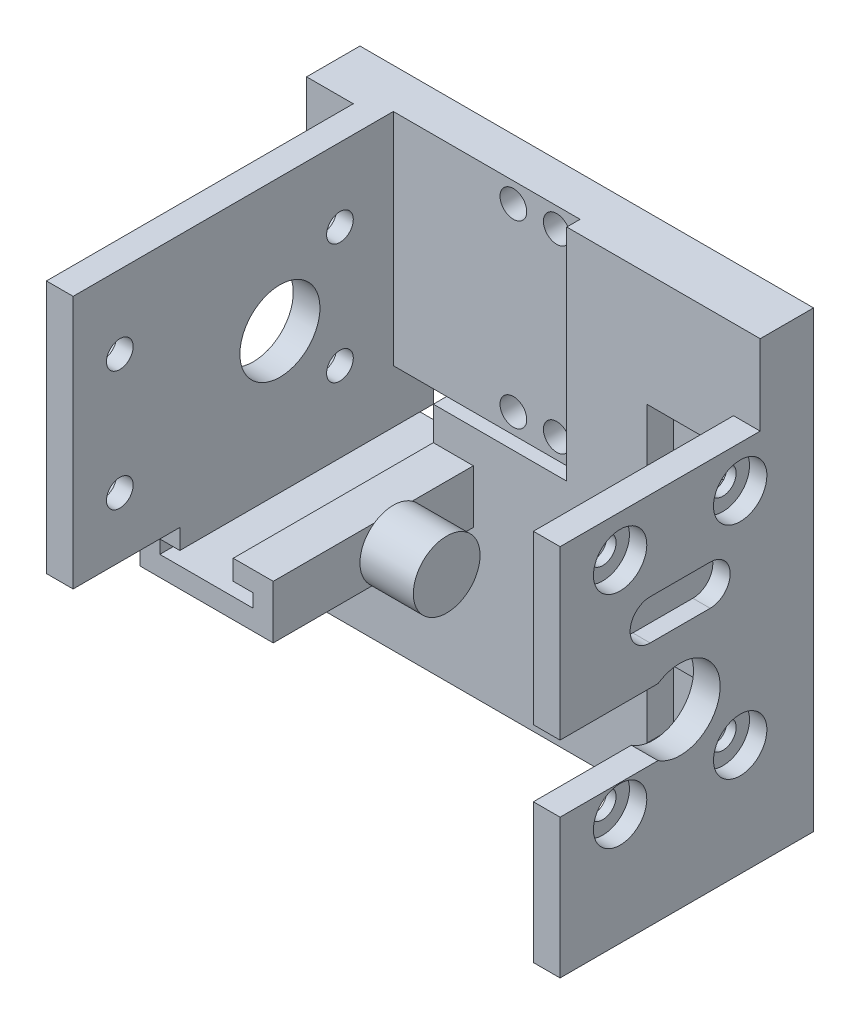
SolidWorks part; units mm, degrees
material "ABS PC"
ref_plane "Front Plane" through (0, 0, 0) normal (0, 0, 1) x (1, 0, 0)
ref_plane "Top Plane" through (0, 0, 0) normal (0, 1, 0) x (1, 0, 0)
ref_plane "Right Plane" through (0, 0, 0) normal (1, 0, 0) x (0, 0, -1)
sketch "Sketch1" plane through (0, 0, 0) normal (0, 0, 1) x (1, 0, 0)
  line L0 (0, 0) -> (0, 60)
  line L1 (0, 60) -> (68, 60)
  line L2 (68, 60) -> (68, 0)
  line L3 (68, 0) -> (0, 0)
  dimension "D1" = 68
  dimension "D2" = 60
extrude "Boss-Extrude1" add sketch "Sketch1" along normal blind 8
sketch "Sketch2" plane through (0, 0, 8) normal (0, 0, 1) x (1, 0, 0)
  line L0 (8, 43) -> (8, 3) construction
  line L1 (8, 3) -> (61, 3) construction
  line L2 (61, 3) -> (61, 43) construction
  line L3 (61, 43) -> (8, 43) construction
  line L4 (0, 60) -> (0, 0) construction
  line L5 (0, 0) -> (68, 0) construction
  line L6 (11, 27) -> (11, 19)
  line L7 (11, 19) -> (8, 19)
  line L8 (8, 19) -> (8, 17)
  line L9 (8, 17) -> (22, 17)
  line L10 (22, 17) -> (22, 19)
  line L11 (22, 19) -> (19, 19)
  line L12 (19, 19) -> (19, 27)
  line L13 (19, 27) -> (11, 27)
  dimension "D1" = 40
  dimension "D2" = 53
  dimension "D3" = 8
  dimension "D4" = 3
  dimension "D5" = 3
  dimension "D6" = 3
  dimension "D7" = 8
  dimension "D8" = 10
  dimension "D9" = 2
  dimension "D10" = 2
  dimension "D11" = 0
  dimension "D12" = 16
sketch "Sketch3" plane through (0, 0, 8) normal (0, 0, 1) x (1, 0, 0)
  line L1 (8, 43) -> (8, 3) construction
  line L2 (25, 14) -> (25, 22)
  line L3 (25, 22) -> (22, 22)
  line L4 (22, 22) -> (22, 30)
  line L5 (22, 30) -> (8, 30)
  line L6 (8, 30) -> (8, 22)
  line L7 (8, 22) -> (5, 22)
  line L8 (5, 22) -> (5, 14)
  line L10 (5, 14) -> (25, 14)
  line L11 (22, 17) -> (22, 19) construction
  line L12 (22, 19) -> (19, 19) construction
  line L13 (19, 19) -> (19, 27) construction
  line L14 (19, 27) -> (11, 27) construction
  line L16 (8, 19) -> (8, 17) construction
  line L17 (11, 19) -> (8, 19) construction
  line L18 (8, 17) -> (22, 17) construction
  point P14 (20.5, 19)
  dimension "D1" = 3
  dimension "D2" = 3
  dimension "D3" = 3
  dimension "D4" = 3
  dimension "D5" = 3
  dimension "D6" = 3
  dimension "D7" = 3
extrude "Boss-Extrude2" add sketch "Sketch3" along normal blind 30
extrude "Cut-Extrude1" cut sketch "Sketch2" against normal through all both and the other way through all
sketch "Sketch4" plane through (0, 0, 38) normal (0, 0, 1) x (1, 0, 0)
  line L0 (8, 30) -> (8, 22)
  line L1 (8, 22) -> (22, 22)
  line L2 (22, 22) -> (22, 30)
  line L3 (22, 30) -> (8, 30)
extrude "Cut-Extrude2" cut sketch "Sketch4" against normal up to surface (30 mm away) up to face at (34, 30, 8)
sketch "Sketch5" plane through (0, 0, 0) normal (0, 0, -1) x (-1, 0, 0)
  line L0 (-11, 1) -> (-11, 41) construction
  line L1 (-11, 41) -> (-61, 41) construction
  line L2 (-61, 41) -> (-61, 1) construction
  line L3 (-61, 1) -> (-11, 1) construction
  line L4 (-11, 27) -> (-11, 19) construction
  line L5 (-8, 17) -> (-22, 17) construction
  line L7 (-61, 1) -> (-53, 1)
  line L8 (-61, 1) -> (-61, 9)
  line L9 (-61, 9) -> (-53, 9)
  line L10 (-53, 1) -> (-53, 9)
  line L11 (-61, 41) -> (-53, 41)
  line L12 (-61, 41) -> (-61, 33)
  line L13 (-61, 33) -> (-53, 33)
  line L14 (-53, 41) -> (-53, 33)
  dimension "D1" = 50
  dimension "D2" = 40
  dimension "D3" = 0
  dimension "D4" = 16
  dimension "D5" = 8
  dimension "D6" = 8
  dimension "D7" = 8
  dimension "D8" = 8
sketch "Sketch6" plane through (0, 0, 8) normal (0, 0, 1) x (1, 0, 0)
  line L0 (53, 41) -> (53, 33) construction
  line L1 (63, 43) -> (51, 43)
  line L2 (63, 43) -> (63, 31)
  line L3 (63, 31) -> (51, 31)
  line L4 (51, 43) -> (51, 31)
  line L5 (63, 11) -> (51, 11)
  line L6 (63, 11) -> (63, -1)
  line L7 (63, -1) -> (51, -1)
  line L8 (51, 11) -> (51, -1)
  line L9 (61, 33) -> (53, 33) construction
  line L10 (61, 41) -> (53, 41) construction
  line L11 (61, 41) -> (61, 33) construction
  line L12 (61, 9) -> (53, 9) construction
  line L13 (53, 1) -> (53, 9) construction
  line L14 (61, 1) -> (53, 1) construction
  line L15 (61, 1) -> (61, 9) construction
  point P12 (57, 33)
  point P19 (57, 9)
  dimension "D1" = 2
  dimension "D2" = 2
  dimension "D3" = 2
  dimension "D4" = 2
  dimension "D5" = 2
  dimension "D6" = 2
  dimension "D7" = 2
  dimension "D8" = 2
sketch "Sketch9" plane through (25, 0, 0) normal (1, 0, 0) x (0, 0, -1)
  line L0 (-8, 14) -> (-8, 22) construction
  circle A0 centre (-20, 17.8811) radius 5
  point P4 (-8, 18)
  dimension "D1" = 10
  dimension "D2" = 12
extrude "Boss-Extrude4" add sketch "Sketch9" along normal blind 8
sketch "Sketch10" plane through (0, 0, 0) normal (0, -1, 0) x (1, 0, 0)
  line L0 (0, 8) -> (68, 8)
  line L1 (68, 8) -> (68, 0) construction
  line L2 (68, 8) -> (68, 0)
  line L3 (68, 0) -> (0, 0)
  line L4 (0, 0) -> (0, 8)
extrude "Boss-Extrude5" add sketch "Sketch10" along normal blind 8
extrude "Cut-Extrude7" cut sketch "Sketch6" against normal blind 4
sketch "Sketch11" plane through (0, 0, 8) normal (0, 0, 1) x (1, 0, 0)
  line L0 (68, 60) -> (0, 60) construction
  line L1 (68, -8) -> (64, -8)
  line L2 (68, -8) -> (68, 60)
  line L3 (68, 60) -> (64, 60)
  line L4 (64, -8) -> (64, 60)
  dimension "D1" = 4
extrude "Boss-Extrude6" add sketch "Sketch11" along normal blind 30
ref_plane "Plane1" through (0, 18, 0) normal (0, -1, 0) x (-1, 0, 0)
sketch "Sketch13" plane through (33, 0, 0) normal (1, 0, 0) x (0, 0, -1)
  circle A0 centre (-20, 17.8811) radius 5
extrude "Cut-Extrude8" cut sketch "Sketch13" along normal up to next
sketch "Sketch14" plane through (68, 0, 0) normal (1, 0, 0) x (0, 0, -1)
  line L0 (0, -8) -> (0, 60) construction
  line L1 (-36, 2.75) -> (-4, 2.75) construction
  line L2 (-36, 2.75) -> (-36, 48.75) construction
  line L3 (-36, 48.75) -> (-4, 48.75) construction
  line L4 (-4, 2.75) -> (-4, 48.75) construction
  line L5 (0, -8) -> (-38, -8) construction
  line L6 (-20, 48.75) -> (-20, 2.75) construction
  line L7 (-24.5, 31.75) -> (-15.5, 31.75) construction
  line L8 (-24.5, 34.75) -> (-15.5, 34.75)
  line L9 (-24.5, 28.75) -> (-15.5, 28.75)
  circle A0 centre (-29, 8.75) radius 4
  circle A1 centre (-11, 8.75) radius 4
  circle A2 centre (-11, 41.75) radius 4
  circle A3 centre (-29, 41.75) radius 4
  arc A4 (-24.5, 34.75) -> (-24.5, 28.75) centre (-24.5, 31.75) ccw
  arc A5 (-15.5, 28.75) -> (-15.5, 34.75) centre (-15.5, 31.75) ccw
  point P20 (-20, 31.75)
  dimension "D5" = 8
  dimension "D6" = 8
  dimension "D7" = 8
  dimension "D8" = 8
  dimension "D19" = 9
  dimension "D1" = 46
  dimension "D2" = 32
  dimension "D3" = 4
  dimension "D4" = 10.75
  dimension "D9" = 7
  dimension "D10" = 7
  dimension "D11" = 7
  dimension "D12" = 7
  dimension "D13" = 7
  dimension "D14" = 6
  dimension "D15" = 7
  dimension "D16" = 6
  dimension "D17" = 14
  dimension "D18" = 20
sketch "Sketch15" plane through (33, 0, 0) normal (1, 0, 0) x (0, 0, -1)
  line L0 (-20, 12.8811) -> (-20, 22.8811) construction
  line L1 (-25, 17.8811) -> (-15, 17.8811) construction
  circle A0 centre (-20, 17.8811) radius 5 construction
extrude "Cut-Extrude9" cut sketch "Sketch14" against normal blind 2.6
sketch "Sketch17" plane through (68, 0, 0) normal (1, 0, 0) x (0, 0, -1)
  circle A0 centre (-11, 41.75) radius 2
  circle A1 centre (-11, 8.75) radius 2
  circle A2 centre (-29, 8.75) radius 2
  circle A3 centre (-29, 41.75) radius 2
  dimension "D1" = 4
  dimension "D2" = 4
  dimension "D3" = 4
  dimension "D4" = 4
extrude "Cut-Extrude10" cut sketch "Sketch17" against normal up to next
sketch "Sketch18" plane through (68, 0, 0) normal (1, 0, 0) x (0, 0, -1)
  line L5 (-44, 22.8811) -> (-44, 12.8811)
  line L7 (-44, 22.8811) -> (-23.3166, 22.8811)
  line L15 (-44, 12.8811) -> (-23.3166, 12.8811)
  arc A3 (-23.3166, 12.8811) -> (-23.3166, 22.8811) centre (-20, 17.8811) ccw
  dimension "D1" = 12
  dimension "D2" = 5
  dimension "D3" = 5
extrude "Cut-Extrude11" cut sketch "Sketch18" against normal up to next
sketch "Sketch19" plane through (0, 0, 4) normal (0, 0, 1) x (1, 0, 0)
  line L0 (51, 11) -> (51, -1) construction
  line L1 (63, 11) -> (51, 11) construction
  line L2 (51, 31) -> (63, 31) construction
  line L3 (51, 43) -> (51, 31) construction
  circle A0 centre (57, 5) radius 2.5
  circle A1 centre (57, 37) radius 2.5
  dimension "D1" = 5
  dimension "D3" = 6
  dimension "D6" = 5
  dimension "D2" = 6
  dimension "D4" = 6
  dimension "D5" = 6
extrude "Cut-Extrude12" cut sketch "Sketch19" against normal up to next
sketch "Sketch20" plane through (0, 0, 38) normal (0, 0, 1) x (1, 0, 0)
  line L0 (68, 22.8811) -> (68, 60) construction
  line L1 (64, 60) -> (68, 60)
  line L2 (64, 60) -> (64, 48)
  line L3 (64, 48) -> (68, 48)
  line L4 (68, 60) -> (68, 48)
  dimension "D1" = 12
extrude "Cut-Extrude13" cut sketch "Sketch20" against normal blind 30
sketch "Sketch21" plane through (0, 0, 8) normal (0, 0, 1) x (1, 0, 0)
  line L0 (51, 43) -> (51, 31) construction
  line L1 (51, 36) -> (22, 36)
  line L2 (51, 36) -> (51, -1)
  line L3 (51, -1) -> (22, -1)
  line L4 (22, 36) -> (22, -1)
  line L5 (51, -1) -> (63, -1) construction
  line L6 (19, 22) -> (19, 27) construction
  line L7 (51, -1) -> (22, 36)
  line L8 (51, 36) -> (22, -1)
  line L9 (63, 43) -> (51, 43) construction
  dimension "D1" = 0
  dimension "D2" = 3
  dimension "D3" = 7
sketch "Sketch22" plane through (0, 0, 0) normal (0, 0, -1) x (-1, 0, 0)
  line L0 (-51, -1) -> (-22, 36) construction
  line L1 (-31.5, 17.5) -> (-34, 21.8301)
  line L2 (-34, 21.8301) -> (-39, 21.8301)
  line L3 (-39, 21.8301) -> (-41.5, 17.5)
  line L4 (-41.5, 17.5) -> (-39, 13.1699)
  line L5 (-39, 13.1699) -> (-34, 13.1699)
  line L6 (-34, 13.1699) -> (-31.5, 17.5)
  line L7 (-51, 36) -> (-22, 36) construction
  circle A0 centre (-36.5, 17.5) radius 4.3301 construction
  dimension "D1" = 10
extrude "Cut-Extrude14" cut sketch "Sketch22" against normal blind 4
sketch "Sketch23" plane through (0, 0, 4) normal (0, 0, -1) x (-1, 0, 0)
  line L0 (-51, -1) -> (-22, 36) construction
  circle A0 centre (-36.5, 17.5) radius 2
  dimension "D1" = 4
extrude "Cut-Extrude15" cut sketch "Sketch23" against normal up to next
ref_plane "Plane2" through (64, 0, 0) normal (1, 0, 0) x (0, 0, -1)
sketch "Sketch24" plane through (0, 0, 8) normal (0, 0, 1) x (1, 0, 0)
  line L0 (68, 60) -> (0, 60) construction
  line L6 (11, 22) -> (7, 22)
  line L7 (11, 22) -> (11, 60)
  line L8 (11, 60) -> (7, 60)
  line L9 (7, 22) -> (7, 60)
  dimension "D2" = 4
extrude "Boss-Extrude7" add sketch "Sketch24" along normal blind 46
sketch "Sketch25" plane through (5, 0, 0) normal (-1, 0, 0) x (0, 0, 1)
  line L0 (38, 14) -> (8, 14) construction
  line L1 (8, 22) -> (8, 14) construction
  circle A0 centre (23, 40) radius 6
  dimension "D3" = 12
  dimension "D1" = 26
  dimension "D2" = 15
extrude "Cut-Extrude16" cut sketch "Sketch25" against normal blind 20
sketch "Sketch27" plane through (0, 60, 0) normal (0, 1, 0) x (1, 0, 0)
  line L1 (11, -8) -> (39, -8)
  line L2 (11, -8) -> (11, -6)
  line L3 (11, -6) -> (39, -6)
  line L4 (39, -8) -> (39, -6)
  dimension "D1" = 28
  dimension "D2" = 2
extrude "Cut-Extrude18" cut sketch "Sketch27" against normal blind 33
sketch "Sketch28" plane through (7, 0, 0) normal (-1, 0, 0) x (0, 0, 1)
  line L0 (8, 60) -> (8, 22) construction
  line L1 (54, 56) -> (8, 56) construction
  line L2 (54, 56) -> (54, 24) construction
  line L3 (54, 24) -> (8, 24) construction
  line L4 (8, 56) -> (8, 24) construction
  line L5 (38, 22) -> (8, 22) construction
  line L6 (54, 40) -> (8, 40) construction
  line L7 (37, 44.5) -> (37, 35.5) construction
  line L8 (40, 44.5) -> (40, 35.5)
  line L9 (34, 44.5) -> (34, 35.5)
  circle A0 centre (14, 49) radius 3
  circle A1 centre (14, 31) radius 3
  circle A2 centre (47, 49) radius 3
  circle A3 centre (47, 31) radius 3
  arc A4 (40, 44.5) -> (34, 44.5) centre (37, 44.5) ccw
  arc A5 (34, 35.5) -> (40, 35.5) centre (37, 35.5) ccw
  point P20 (37, 40)
  dimension "D9" = 6
  dimension "D10" = 6
  dimension "D13" = 6
  dimension "D16" = 6
  dimension "D1" = 0
  dimension "D2" = 2
  dimension "D3" = 32
  dimension "D4" = 46
  dimension "D5" = 6
  dimension "D6" = 7
  dimension "D7" = 7
  dimension "D8" = 6
  dimension "D11" = 7
  dimension "D12" = 7
  dimension "D14" = 7
  dimension "D15" = 7
  dimension "D17" = 14
  dimension "D18" = 20
  dimension "D19" = 9
extrude "Cut-Extrude19" cut sketch "Sketch28" against normal blind 1.5
sketch "Sketch29" plane through (11, 0, 0) normal (1, 0, 0) x (0, 0, -1)
  circle A0 centre (-47, 49) radius 2
  circle A1 centre (-47, 31) radius 2
  circle A2 centre (-14, 49) radius 2
  circle A3 centre (-14, 31) radius 2
  dimension "D1" = 4
  dimension "D2" = 4
  dimension "D3" = 4
  dimension "D4" = 4
extrude "Cut-Extrude20" cut sketch "Sketch29" against normal up to next
sketch "Sketch30" plane through (0, 0, 6) normal (0, 0, 1) x (1, 0, 0)
  line L0 (11, 27) -> (11, 60) construction
  line L1 (39, 60) -> (11, 60) construction
  line L2 (19, 27) -> (11, 27) construction
  line L3 (39, 27) -> (19, 27) construction
  circle A0 centre (29, 30) radius 2
  circle A1 centre (29, 57) radius 2
  circle A2 centre (35.5, 30) radius 2
  circle A3 centre (35.5, 57) radius 2
  dimension "D1" = 4
  dimension "D2" = 4
  dimension "D3" = 4
  dimension "D4" = 4
  dimension "D5" = 18
  dimension "D6" = 3
  dimension "D7" = 3
  dimension "D8" = 18
  dimension "D9" = 3
  dimension "D10" = 24.5
  dimension "D11" = 3
  dimension "D12" = 24.5
extrude "Cut-Extrude21" cut sketch "Sketch30" against normal up to next
sketch "Sketch33" plane through (0, 0, 0) normal (-1, 0, 0) x (0, 0, 1)
  line L0 (0, 60) -> (0, -8) construction
  line L1 (0, 23) -> (-5, 23)
  line L2 (0, 23) -> (0, 18)
  line L3 (0, 18) -> (-5, 18)
  line L4 (-5, 23) -> (-5, 18)
  line L6 (0, 7) -> (-5, 7)
  line L7 (0, 7) -> (0, 2)
  line L8 (0, 2) -> (-5, 2)
  line L9 (-5, 7) -> (-5, 2)
  dimension "D1" = 5
  dimension "D2" = 5
  dimension "D3" = 5
  dimension "D4" = 5
  dimension "D5" = 11
  dimension "D6" = 10
extrude "Boss-Extrude9" add sketch "Sketch33" against normal blind 2 separate body
sketch "Sketch34" plane through (0, 0, 0) normal (-1, 0, 0) x (0, 0, 1)
  line L0 (-5, 2) -> (0, 2) construction
  line L1 (0, 60) -> (0, -8) construction
  line L2 (0, 18) -> (0, 23) construction
  line L3 (0, 23) -> (-5, 23) construction
  circle A0 centre (-2.5, 20.5) radius 1.5
  circle A1 centre (-2.5, 4.5) radius 1.5
  dimension "D1" = 3
  dimension "D2" = 3
  dimension "D3" = 2.5
  dimension "D4" = 2.5
  dimension "D5" = 2.5
  dimension "D6" = 2.5
extrude "Cut-Extrude23" cut sketch "Sketch34" against normal up to next (2 mm away)
sketch "Sketch35" plane through (0, -8, 0) normal (0, -1, 0) x (-1, 0, 0)
  line L0 (0, 0) -> (-68, 0) construction
  line L1 (0, 0) -> (-5, 0)
  line L2 (0, 0) -> (0, 5)
  line L3 (0, 5) -> (-5, 5)
  line L4 (-5, 0) -> (-5, 5)
  line L5 (-16, 0) -> (-21, 0)
  line L6 (-16, 0) -> (-16, 5)
  line L7 (-16, 5) -> (-21, 5)
  line L8 (-21, 0) -> (-21, 5)
  dimension "D1" = 5
  dimension "D2" = 5
  dimension "D3" = 11
  dimension "D4" = 5
  dimension "D5" = 5
extrude "Boss-Extrude10" add sketch "Sketch35" against normal blind 2
sketch "Sketch36" plane through (0, -8, 0) normal (0, -1, 0) x (-1, 0, 0)
  line L0 (-21, 5) -> (-21, 0) construction
  line L1 (-16, 5) -> (-21, 5) construction
  line L2 (0, -8) -> (0, 5) construction
  line L3 (0, 5) -> (-5, 5) construction
  circle A0 centre (-2.5, 2.5) radius 1.5
  circle A1 centre (-18.5, 2.5) radius 1.5
  dimension "D1" = 3
  dimension "D2" = 3
  dimension "D3" = 2.5
  dimension "D4" = 2.5
  dimension "D5" = 2.5
  dimension "D6" = 2.5
extrude "Cut-Extrude24" cut sketch "Sketch36" against normal up to next (2 mm away)
ref_plane "Plane3" through (0, 0, 30) normal (0, 0, 1) x (1, 0, 0)
ref_plane "Plane4" through (38, 0, 0) normal (1, 0, 0) x (0, 0, -1)
